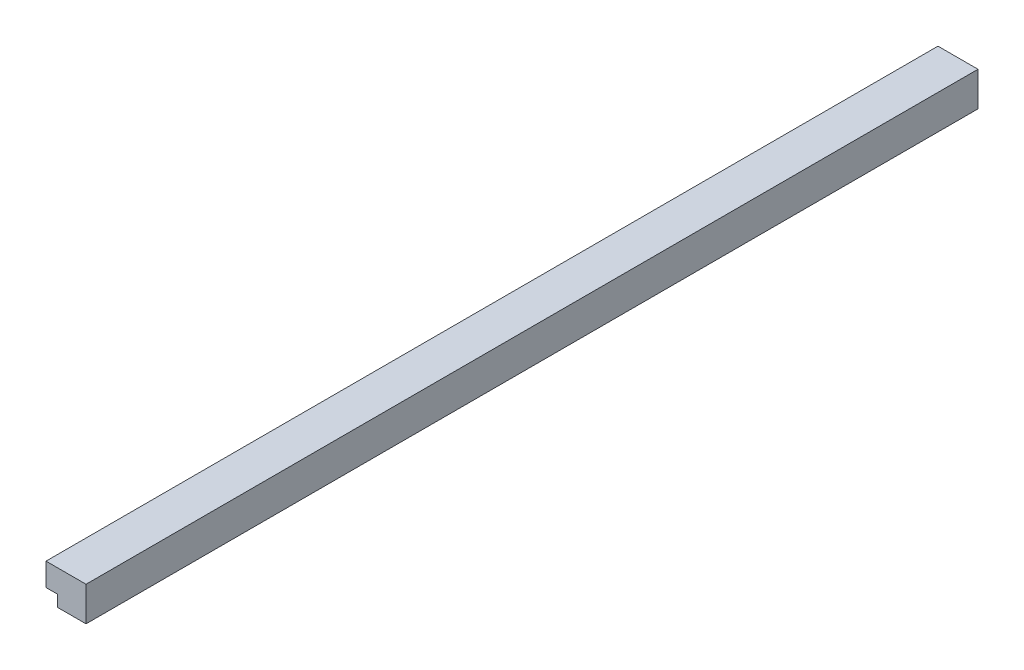
SolidWorks part; units mm, degrees
material "Сосна"
ref_plane "Спереди" through (0, 0, 0) normal (0, 0, 1) x (1, 0, 0)
ref_plane "Сверху" through (0, 0, 0) normal (0, 1, 0) x (1, 0, 0)
ref_plane "Справа" through (0, 0, 0) normal (1, 0, 0) x (0, 0, -1)
sketch "Эскиз1" plane through (0, 0, 0) normal (0, 0, -1) x (1, 0, 0)
  line L0 (0, 20) -> (10, 20)
  line L1 (0, 0) -> (35, 0)
  line L2 (0, 0) -> (0, 20)
  line L3 (10, 30) -> (35, 30)
  line L4 (35, 0) -> (35, 30)
  line L5 (10, 20) -> (10, 30)
  dimension "D1" = 35
  dimension "D2" = 30
  dimension "D3" = 10
  dimension "D4" = 10
extrude "Бобышка-Вытянуть1" add sketch "Эскиз1" along normal blind 780
